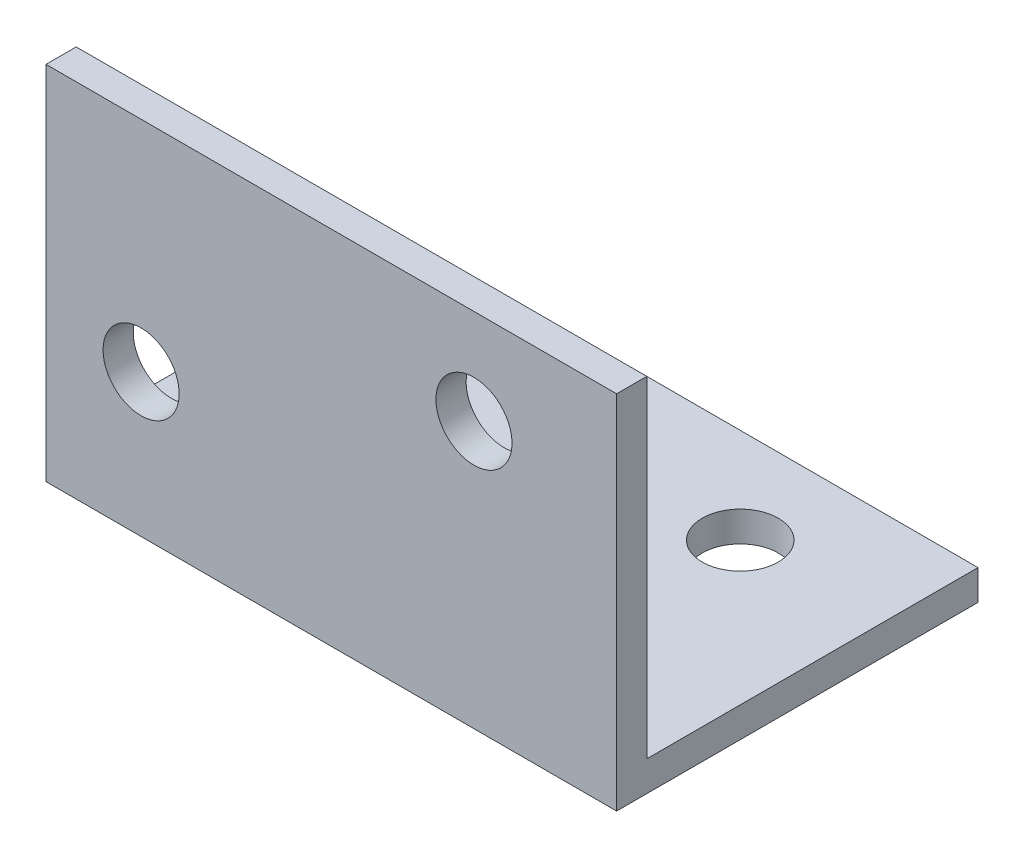
SolidWorks part; units mm, degrees
ref_plane "Front Plane" through (0, 0, 0) normal (0, 0, 1) x (1, 0, 0)
ref_plane "Top Plane" through (0, 0, 0) normal (0, 1, 0) x (1, 0, 0)
ref_plane "Right Plane" through (0, 0, 0) normal (1, 0, 0) x (0, 0, -1)
sketch "Sketch1" plane through (0, 0, 0) normal (0, 0, 1) x (1, 0, 0)
  line L1 (0, 0) -> (60, 0)
  line L2 (0, 0) -> (0, 38)
  line L3 (0, 38) -> (60, 38)
  line L4 (60, 0) -> (60, 38)
  dimension "D1" = 60
  dimension "D2" = 38
extrude "Boss-Extrude1" add sketch "Sketch1" along normal blind 3.175
sketch "Sketch2" plane through (0, 0, 0) normal (0, 0, -1) x (-1, 0, 0)
  line L0 (0, 38) -> (0, 0) construction
  line L1 (-60, 0) -> (0, 0)
  line L2 (-60, 0) -> (-60, 3.175)
  line L3 (-60, 3.175) -> (0, 3.175)
  line L4 (0, 0) -> (0, 3.175)
  dimension "D1" = 3.175
extrude "Boss-Extrude2" add sketch "Sketch2" along normal blind 34.825
sketch "Sketch3" plane through (0, 0, 0) normal (0, 0, -1) x (-1, 0, 0)
  line L0 (-60, 38) -> (0, 38) construction
  line L1 (-60, 3.175) -> (-60, 38) construction
  line L2 (-60, 0) -> (0, 0) construction
  line L3 (0, 38) -> (0, 3.175) construction
  circle A0 centre (-45, 28) radius 4
  circle A1 centre (-10, 15) radius 4
  point P10 (0, 0)
  dimension "D1" = 8
  dimension "D4" = 15
  dimension "D2" = 10
  dimension "D3" = 15
  dimension "D5" = 10
extrude "Cut-Extrude1" cut sketch "Sketch3" against normal through all
sketch "Sketch4" plane through (0, 3.175, 0) normal (0, 1, 0) x (1, 0, 0)
  line L0 (0, 34.825) -> (60, 34.825) construction
  line L1 (60, 34.825) -> (60, 0) construction
  line L2 (60, -3.175) -> (0, -3.175) construction
  line L3 (0, 34.825) -> (0, 0) construction
  circle A0 centre (45, 24.825) radius 4
  circle A1 centre (10, 11.825) radius 4
  dimension "D1" = 8
  dimension "D2" = 10
  dimension "D3" = 15
  dimension "D4" = 15
  dimension "D5" = 10
extrude "Cut-Extrude2" cut sketch "Sketch4" against normal through all
